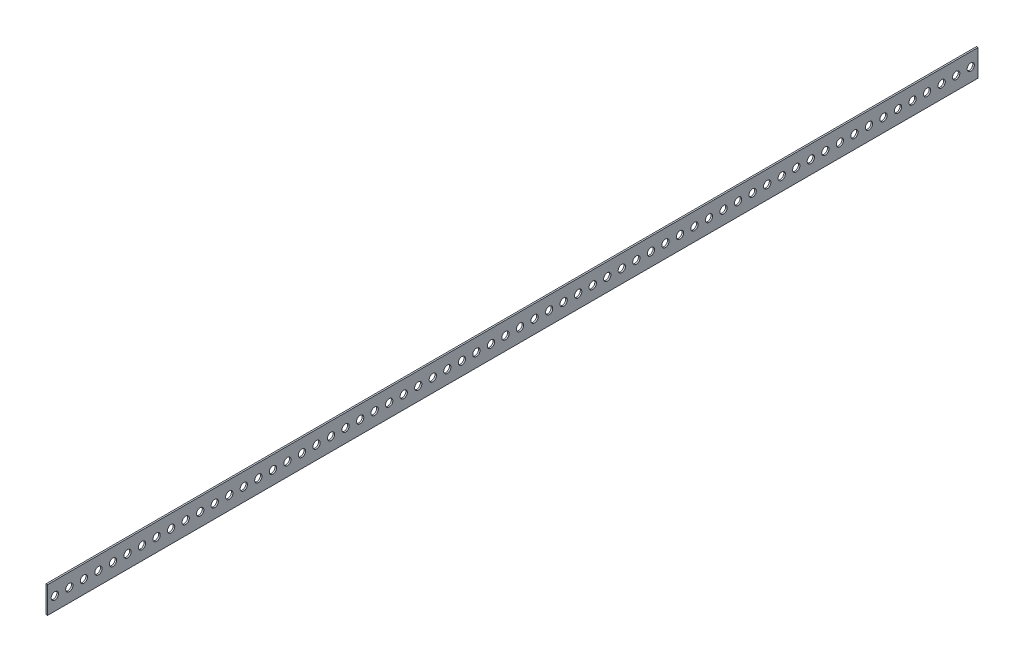
SolidWorks part; units mm, degrees
ref_plane "Front Plane" through (0, 0, 0) normal (0, 0, 1) x (1, 0, 0)
ref_plane "Top Plane" through (0, 0, 0) normal (0, 1, 0) x (1, 0, 0)
ref_plane "Right Plane" through (0, 0, 0) normal (1, 0, 0) x (0, 0, -1)
sketch "Sketch1" plane through (0, 0, 0) normal (0, 0, 1) x (1, 0, 0)
  line L1 (2.032, 0) -> (0, 0)
  line L2 (2.032, 0) -> (2.032, 34.925)
  line L3 (2.032, 34.925) -> (0, 34.925)
  line L4 (0, 0) -> (0, 34.925)
  dimension "D2" = 2.032
  dimension "D1" = 34.925
extrude "Boss-Extrude1" add sketch "Sketch1" along normal mid plane 1219.2
sketch "Sketch2" plane through (0, 0, 0) normal (-1, 0, 0) x (0, 0, 1)
  line L0 (600.075, 17.4625) -> (581.025, 17.4625) construction
  line L1 (600.075, 17.4625) -> (609.6, 17.4625) construction
  line L2 (609.6, 0) -> (609.6, 34.925) construction
  circle A0 centre (600.075, 17.4625) radius 4.7625
  dimension "D1" = 9.525
  dimension "D2" = 19.05
  dimension "D3" = 9.525
extrude "Cut-Extrude1" cut sketch "Sketch2" against normal up to next
pattern_linear "LPattern1" count 64 spacing 19.05 along (0, 0, -1) of "Cut-Extrude1"
equation "\"D3@Sketch2\" = \"D2@Sketch2\" / 2"
equation "\"D3@LPattern1\" = \"D2@Sketch2\""
equation "\"D1@LPattern1\" = \"D1@Boss-Extrude1\" / \"D2@Sketch2\""
